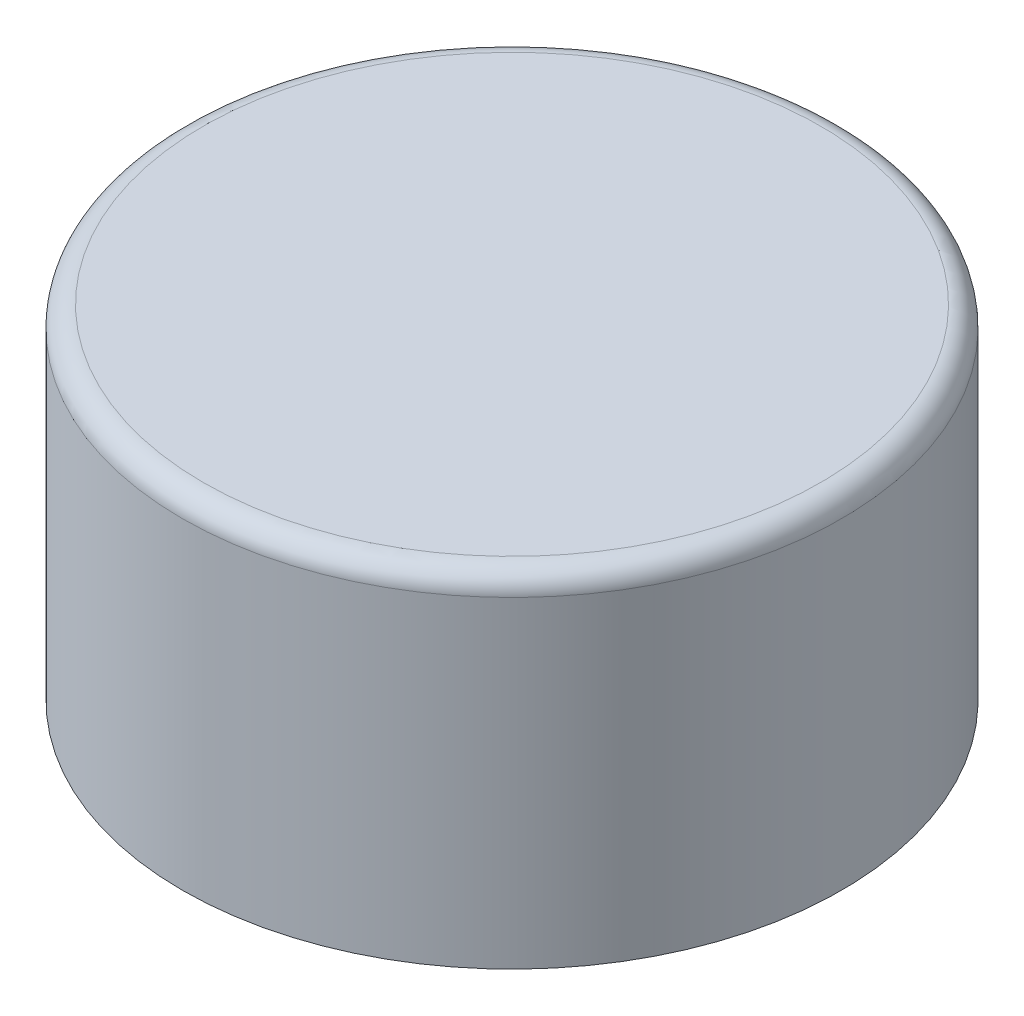
SolidWorks part; units mm, degrees
ref_plane "Front Plane" through (0, 0, 0) normal (0, 0, 1) x (1, 0, 0)
ref_plane "Top Plane" through (0, 0, 0) normal (0, 1, 0) x (1, 0, 0)
ref_plane "Right Plane" through (0, 0, 0) normal (1, 0, 0) x (0, 0, -1)
sketch "Sketch1" plane through (0, 0, 0) normal (0, 1, 0) x (1, 0, 0)
  circle A0 centre (0, 0) radius 7.493
  dimension "D1" = 14.986
extrude "Boss-Extrude1" add sketch "Sketch1" along normal blind 7.2644
sketch "Sketch2" plane through (0, 7.2644, 0) normal (0, 1, 0) x (1, 0, 0)
  circle A0 centre (0, 0) radius 20.0533
  dimension "D1" = 40.1066
extrude "Boss-Extrude2" add sketch "Sketch2" along normal blind 20.8534
fillet "Fillet1" radius 1.27 1 edges at (0, 28.1178, 20.0533)
